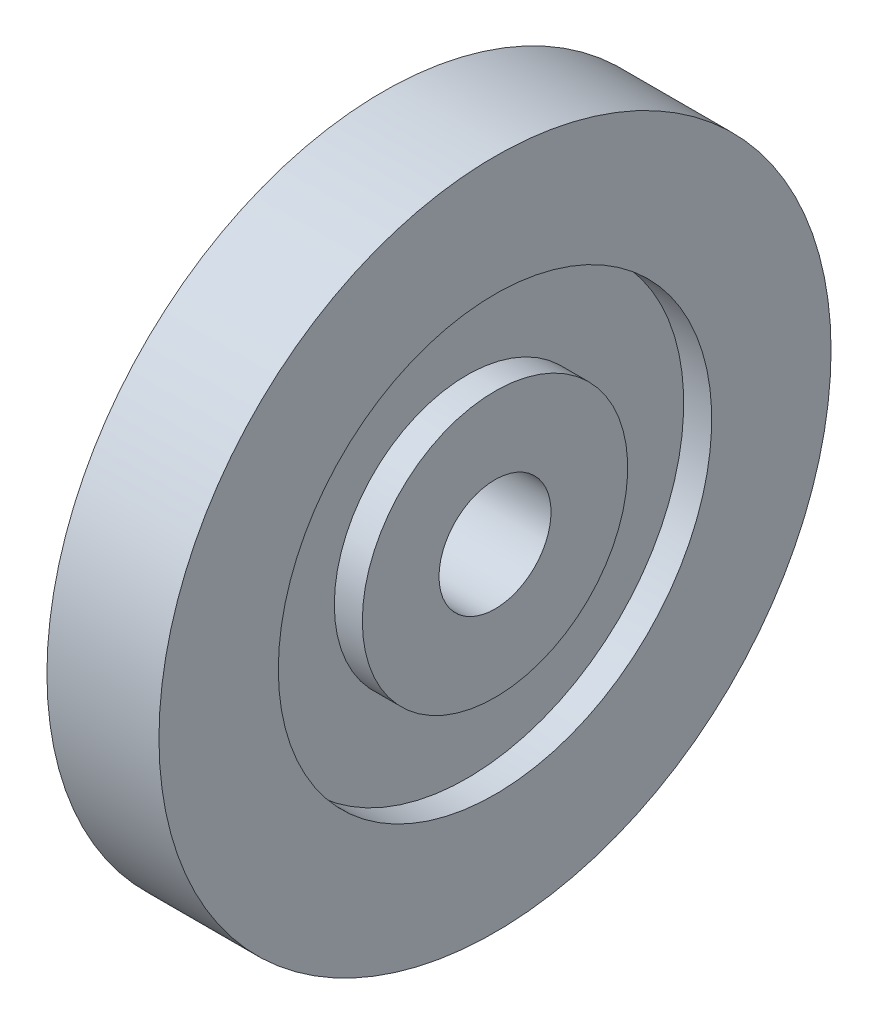
SolidWorks part; units mm, degrees
material "1.2083 (X40Cr14)"
ref_plane "Plan de face" through (0, 0, 0) normal (0, 0, 1) x (1, 0, 0)
ref_plane "Plan de dessus" through (0, 0, 0) normal (0, 1, 0) x (1, 0, 0)
ref_plane "Plan de droite" through (0, 0, 0) normal (1, 0, 0) x (0, 0, -1)
sketch "Esquisse1" plane through (0, 0, 0) normal (0, 0, 1) x (1, 0, 0)
  line L0 (-2, -10.4298) -> (2, -10.4298)
  line L1 (2, -10.4298) -> (2, -7.6914)
  line L2 (2, -7.6914) -> (1, -7.6914)
  line L3 (0, -12) -> (0, 8) construction
  line L4 (2, -12.4298) -> (6, -12.4298) construction
  line L5 (3.8867, 0) -> (-7.9999, 0) construction
  line L6 (-2, -7.6914) -> (-1, -7.6914)
  line L7 (-2, -10.4298) -> (-2, -7.6914)
  line L8 (-2, -0.4298) -> (-2, -4.6914)
  line L9 (-2, -4.6914) -> (-1, -4.6914)
  line L10 (2, -4.6914) -> (1, -4.6914)
  line L11 (2, -0.4298) -> (2, -4.6914)
  line L12 (-2, -0.4298) -> (2, -0.4298)
  line L13 (1, -7.6914) -> (1, -4.6914)
  line L14 (-1, -7.6914) -> (-1, -4.6914)
  dimension "D4" = 4
  dimension "D1" = 2
  dimension "D2" = 3
  dimension "D3" = 12
  dimension "D6" = 1
  dimension "D7" = 1
revolve "Revolve1" add sketch "Esquisse1" angle 360 about L4
